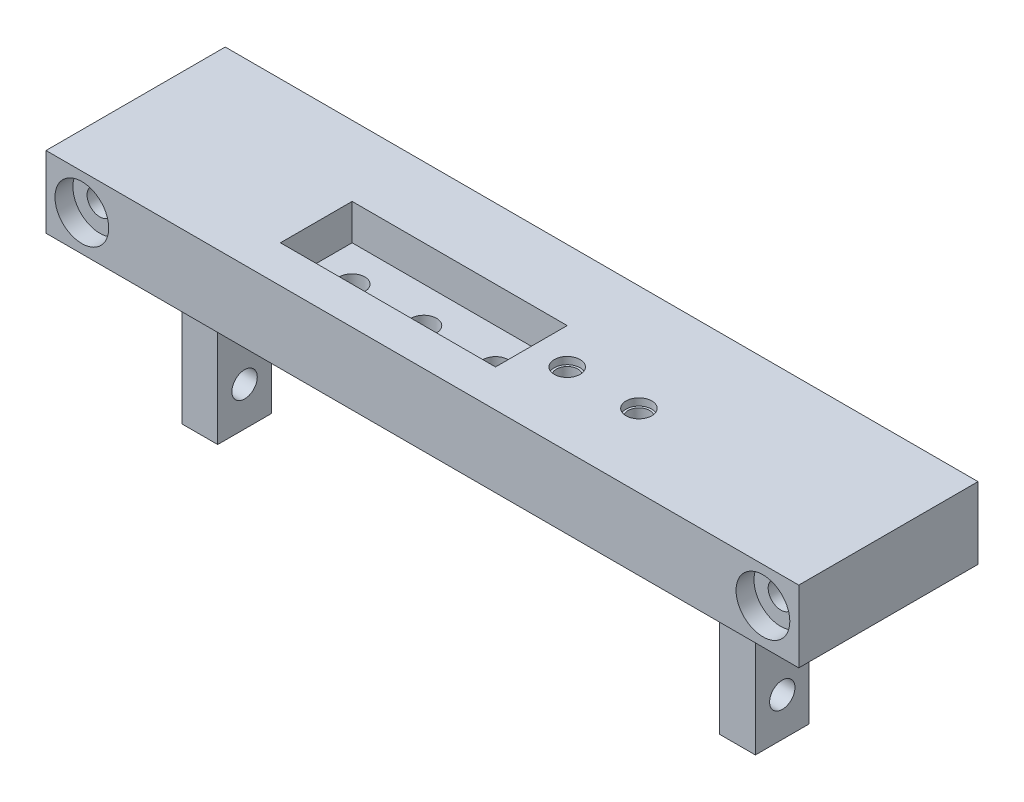
SolidWorks part; units mm, degrees
ref_plane "Front Plane" through (0, 0, 0) normal (0, 0, 1) x (1, 0, 0)
ref_plane "Top Plane" through (0, 0, 0) normal (0, 1, 0) x (1, 0, 0)
ref_plane "Right Plane" through (0, 0, 0) normal (1, 0, 0) x (0, 0, -1)
sketch "Sketch1" plane through (0, 0, 0) normal (0, 1, 0) x (1, 0, 0)
  line L1 (0, 0) -> (133.35, 0)
  line L2 (0, 0) -> (0, 31.75)
  line L3 (0, 31.75) -> (133.35, 31.75)
  line L4 (133.35, 0) -> (133.35, 31.75)
  dimension "D1" = 133.35
  dimension "D2" = 31.75
extrude "Boss-Extrude1" add sketch "Sketch1" along normal blind 12.7
hole_wizard "CBORE for #8 Binding Head Machine Screw1" positions "Sketch2" profile "Sketch3" counterbore size "#8" standard "ANSI Inch" end condition through all
sketch "Sketch2" plane through (0, 0, 0) normal (0, 0, 1) x (1, 0, 0)
  line L0 (0, 12.7) -> (133.35, 12.7) construction
  line L1 (0, 12.7) -> (0, 0) construction
  point P0 (6.35, 6.35)
  point P2 (127, 6.35)
  dimension "D1" = 6.35
  dimension "D2" = 120.65
  dimension "D3" = 6.35
sketch "Sketch3" plane through (6.35, 6.35, 0) normal (1, 0, 0) x (0, -1, 0)
  line L0 (0, 0) -> (0, 31.75)
  line L1 (0, 31.75) -> (2.2479, 31.75)
  line L3 (2.2479, 31.75) -> (2.2479, 3.175)
  line L4 (2.2479, 3.175) -> (4.7625, 3.175)
  line L5 (4.7625, 3.175) -> (4.7625, 0)
  line L7 (4.7625, 0) -> (0, 0)
  line L11 (0, -6.35) -> (0, 107.95) construction
  dimension "Thru Hole Dia." = 4.4958
  dimension "Thru Hole Depth" = 31.75
  dimension "C'Bore Dia." = 9.525
  dimension "C'Bore Depth" = 3.175
hole_wizard "#8 (0.199) Diameter Hole1" positions "Sketch4" profile "Sketch5" hole size "#8" standard "ANSI Inch" end condition through all
sketch "Sketch4" plane through (0, 12.7, 0) normal (0, 1, 0) x (1, 0, 0)
  line L0 (133.35, 31.75) -> (0, 31.75) construction
  line L1 (133.35, 0) -> (133.35, 31.75) construction
  point P0 (66.675, 12.954)
  dimension "D1" = 18.796
  dimension "D2" = 66.675
sketch "Sketch5" plane through (66.675, 12.7, -12.954) normal (1, 0, 0) x (0, 0, 1)
  line L0 (0, 0) -> (0, 12.7)
  line L1 (0, 12.7) -> (2.2479, 12.7)
  line L2 (2.2479, 12.7) -> (2.2479, 0)
  line L5 (2.2479, 0) -> (0, 0)
  line L11 (0, -6.35) -> (0, 107.95) construction
  dimension "Thru Hole Dia." = 4.4958
  dimension "Thru Hole Depth" = 12.7
sketch "Sketch6" plane through (0, 0, 0) normal (0, -1, 0) x (1, 0, 0)
  line L0 (0, -31.75) -> (0, 0) construction
  line L1 (111.125, -8.1915) -> (117.475, -8.1915)
  line L2 (111.125, -8.1915) -> (111.125, -17.7165)
  line L3 (111.125, -17.7165) -> (117.475, -17.7165)
  line L4 (117.475, -8.1915) -> (117.475, -17.7165)
  line L5 (15.875, -8.1915) -> (22.225, -8.1915)
  line L6 (15.875, -8.1915) -> (15.875, -17.7165)
  line L7 (15.875, -17.7165) -> (22.225, -17.7165)
  line L8 (22.225, -8.1915) -> (22.225, -17.7165)
  line L9 (133.35, 0) -> (133.35, -31.75) construction
  line L10 (133.35, -31.75) -> (0, -31.75) construction
  dimension "D1" = 6.35
  dimension "D2" = 9.525
  dimension "D3" = 6.35
  dimension "D4" = 9.525
  dimension "D5" = 15.875
  dimension "D6" = 15.875
  dimension "D7" = 14.0335
  dimension "D8" = 14.0335
extrude "Boss-Extrude2" add sketch "Sketch6" along normal blind 25.4
hole_wizard "#8 (0.199) Diameter Hole2" positions "Sketch7" profile "Sketch8" hole size "#8" standard "ANSI Inch" end condition through all
sketch "Sketch7" plane through (117.475, 0, 0) normal (1, 0, 0) x (0, 0, -1)
  line L0 (17.7165, 0) -> (8.1915, 0) construction
  line L1 (8.1915, -25.4) -> (8.1915, 0) construction
  point P0 (12.954, -5.842)
  point P2 (12.954, -18.542)
  dimension "D1" = 5.842
  dimension "D2" = 4.7625
  dimension "D3" = 12.7
sketch "Sketch8" plane through (117.475, -5.842, -12.954) normal (0, 1, 0) x (0, 0, -1)
  line L0 (0, 0) -> (0, 117.475)
  line L1 (0, 117.475) -> (2.2479, 117.475)
  line L2 (2.2479, 117.475) -> (2.2479, 0)
  line L5 (2.2479, 0) -> (0, 0)
  line L11 (0, -6.35) -> (0, 107.95) construction
  dimension "Thru Hole Dia." = 4.4958
  dimension "Thru Hole Depth" = 117.475
hole_wizard "CBORE for #6 Binding Head Machine Screw1" positions "Sketch11" profile "Sketch10" counterbore size "#6" standard "ANSI Inch" end condition through all
sketch "Sketch11" plane through (0, 0, 0) normal (0, -1, 0) x (-1, 0, 0)
  line L1 (-133.35, 31.75) -> (0, 31.75) construction
  circle A0 centre (-66.675, 12.954) radius 2.2479 construction
  point P0 (-79.375, 12.954)
  point P2 (-92.075, 12.954)
  dimension "D1" = 18.796
  dimension "D2" = 12.7
  dimension "D3" = 12.7
sketch "Sketch10" plane through (79.375, 0, -12.954) normal (1, 0, 0) x (0, 0, -1)
  line L0 (0, 0) -> (0, 12.7)
  line L1 (0, 12.7) -> (1.8986, 12.7)
  line L3 (1.8986, 12.7) -> (1.8986, 6.35)
  line L4 (1.8986, 6.35) -> (3.9688, 6.35)
  line L5 (3.9688, 6.35) -> (3.9688, 0)
  line L7 (3.9688, 0) -> (0, 0)
  line L11 (0, -6.35) -> (0, 107.95) construction
  dimension "Thru Hole Dia." = 3.7973
  dimension "Thru Hole Depth" = 12.7
  dimension "C'Bore Dia." = 7.9375
  dimension "C'Bore Depth" = 6.35
sketch "Sketch12" plane through (0, 12.7, 0) normal (0, 1, 0) x (1, 0, 0)
  circle A0 centre (79.375, 12.954) radius 2.286
  circle A1 centre (92.075, 12.954) radius 2.286
extrude "Cut-Extrude1" cut sketch "Sketch12" against normal blind 1.27
sketch "Sketch13" plane through (0, 12.7, 0) normal (0, 1, 0) x (1, 0, 0)
  line L0 (66.675, 12.954) -> (66.675, 19.304)
  line L1 (66.675, 19.304) -> (34.925, 19.304)
  line L2 (34.925, 19.304) -> (34.925, 6.604)
  line L3 (34.925, 6.604) -> (66.675, 6.604)
  line L4 (66.675, 6.604) -> (66.675, 12.954)
  line L5 (66.675, 19.304) -> (73.025, 19.304)
  line L6 (73.025, 19.304) -> (73.025, 6.604)
  line L7 (73.025, 6.604) -> (66.675, 6.604)
  circle M10 centre (66.675, 12.954) radius 2.2479
  dimension "D1" = 6.35
  dimension "D2" = 6.35
  dimension "D3" = 31.75
  dimension "D4" = 6.35
extrude "Cut-Extrude2" cut sketch "Sketch13" against normal blind 6.35 contours L3 L4 L0 L1 L2 M10 | L7 L6 L5 L0 L4 M10
hole_wizard "#8 (0.199) Diameter Hole3" positions "Sketch14" profile "Sketch15" hole size "#8" standard "ANSI Inch" end condition through all
sketch "Sketch14" plane through (0, 6.35, 0) normal (0, 1, 0) x (1, 0, 0)
  line L0 (73.025, 19.304) -> (34.925, 19.304) construction
  circle A0 centre (66.675, 12.954) radius 2.2479 construction
  point P0 (53.975, 12.954)
  point P2 (41.275, 12.954)
  dimension "D1" = 12.7
  dimension "D2" = 12.7
  dimension "D3" = 6.35
sketch "Sketch15" plane through (53.975, 6.35, -12.954) normal (1, 0, 0) x (0, 0, 1)
  line L0 (0, 0) -> (0, 31.75)
  line L1 (0, 31.75) -> (2.2479, 31.75)
  line L2 (2.2479, 31.75) -> (2.2479, 0)
  line L5 (2.2479, 0) -> (0, 0)
  line L11 (0, -6.35) -> (0, 107.95) construction
  dimension "Thru Hole Dia." = 4.4958
  dimension "Thru Hole Depth" = 31.75
